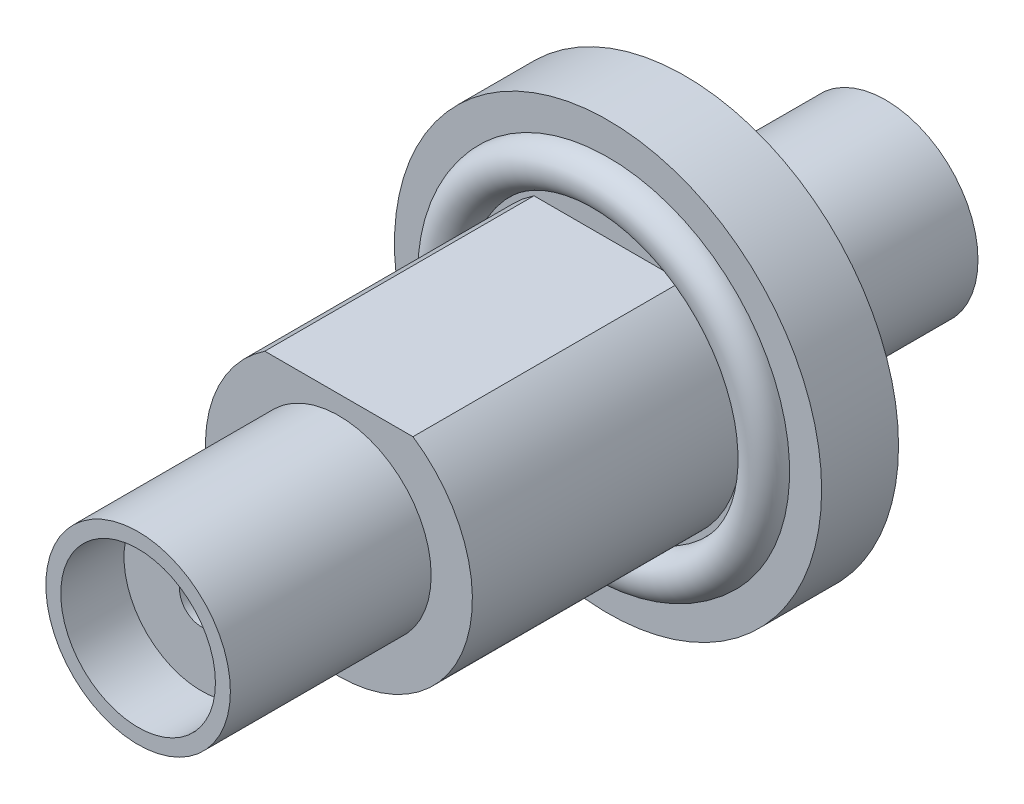
SolidWorks part; units mm, degrees
ref_plane "Front" through (0, 0, 0) normal (0, 0, 1) x (1, 0, 0)
ref_plane "Top" through (0, 0, 0) normal (0, 1, 0) x (1, 0, 0)
ref_plane "Right" through (0, 0, 0) normal (1, 0, 0) x (0, 0, -1)
ref_axis "Axis1" through (0, 0, -7.0802) along (0, 0, 1)
sketch "Sketch1" plane through (0, 0, 0) normal (0, 0, 1) x (1, 0, 0)
  circle A0 centre (0, 0) radius 6.35
  dimension "D1" = 12.7
extrude "Extrude1" add sketch "Sketch1" along normal blind 2.286
sketch "Sketch2" plane through (0, 0, 0) normal (0, 0, -1) x (-1, 0, 0)
  circle A0 centre (0, 0) radius 2.7432
  dimension "D1" = 5.4864
extrude "Extrude2" add sketch "Sketch2" along normal blind 5.969
cosmetic thread "Cosmetic Thread1" parameters "D1"=4.318, "D2"=5.2121
sketch "Sketch3" plane through (0, 0, -5.969) normal (0, 0, -1) x (-1, 0, 0)
  circle A0 centre (0, 0) radius 2.2987
  dimension "D1" = 4.5974
extrude "Cut-Extrude1" cut sketch "Sketch3" against normal blind 1.8796
sketch "Sketch4" plane through (0, 0, -4.0894) normal (0, 0, -1) x (-1, 0, 0)
  circle A0 centre (0, 0) radius 0.6477
  dimension "D1" = 1.2954
extrude "Cut-Extrude2" cut sketch "Sketch4" against normal up to surface (4.0894 mm away) up to face at (6.35, 0, 0)
sketch "Sketch5" plane through (0, 0, 2.286) normal (0, 0, 1) x (1, 0, 0)
  circle A0 centre (0, 0) radius 3.9688
  dimension "D1" = 7.9375
extrude "Extrude3" add sketch "Sketch5" along normal blind 8.001
cosmetic thread "Cosmetic Thread2" parameters "D2"=7.9248
sketch "Sketch6" plane through (0, 0, 10.287) normal (0, 0, 1) x (1, 0, 0)
  circle A0 centre (0, 0) radius 2.7432
  dimension "D1" = 5.4864
extrude "Extrude4" add sketch "Sketch6" along normal blind 5.969
cosmetic thread "Cosmetic Thread4" parameters "D1"=4.318, "D2"=5.2121
sketch "Sketch7" plane through (0, 0, 16.256) normal (0, 0, 1) x (1, 0, 0)
  circle A0 centre (0, 0) radius 2.2987
  dimension "D1" = 4.5974
extrude "Cut-Extrude3" cut sketch "Sketch7" against normal blind 1.8796
sketch "Sketch8" plane through (0, 0, 14.3764) normal (0, 0, 1) x (1, 0, 0)
  circle A0 centre (0, 0) radius 0.6477
  dimension "D1" = 1.2954
extrude "Cut-Extrude4" cut sketch "Sketch8" against normal up to surface (12.0904 mm away) up to face at (6.35, 0, 2.286)
sketch "Sketch9" plane through (0, 0, 0) normal (1, 0, 0) x (0, 0, -1)
  line L0 (-2.286, 6.35) -> (-2.286, -6.35) construction
  line L1 (-2.286, 5.3975) -> (-1.651, 5.3975)
  line L2 (-2.286, 5.3975) -> (-2.286, 4.1275)
  line L3 (-2.286, 4.1275) -> (-1.651, 4.1275)
  line L4 (-1.651, 5.3975) -> (-1.651, 4.1275)
  line L5 (0, 6.35) -> (-2.286, 6.35) construction
  dimension "D1" = 0.9525
  dimension "D2" = 1.27
  dimension "D3" = 0.635
revolve "Cut-Revolve1" cut sketch "Sketch9" angle 360 about axis through (0, 0, -7.0802) along (0, 0, 1)
ref_plane "Plane1" through (0, 3.302, 0) normal (0, 1, 0) x (-1, 0, 0)
sketch "Sketch12" plane through (0, 3.302, 0) normal (0, 1, 0) x (-1, 0, 0)
  line L0 (3.9688, 2.286) -> (3.9688, 10.287) construction
  line L1 (3.9688, 2.286) -> (-3.9688, 2.286)
  line L2 (3.9688, 2.286) -> (3.9688, 10.287)
  line L3 (3.9688, 10.287) -> (-3.9688, 10.287)
  line L4 (-3.9688, 2.286) -> (-3.9688, 10.287)
  line L6 (6.35, 2.286) -> (-6.35, 2.286) construction
extrude "Cut-Extrude5" cut sketch "Sketch12" along normal through all
sketch "Sketch10" plane through (0, 0, 0) normal (1, 0, 0) x (0, 0, -1)
  line L0 (-2.286, 6.35) -> (-2.286, -6.35) construction
  line L1 (0, 6.35) -> (-2.286, 6.35) construction
  circle A0 centre (-2.286, 4.7625) radius 0.635
  dimension "D1" = 1.27
  dimension "D2" = 1.5875
revolve "Revolve1" add sketch "Sketch10" angle 360 about axis through (0, 0, -7.0802) along (0, 0, 1)
